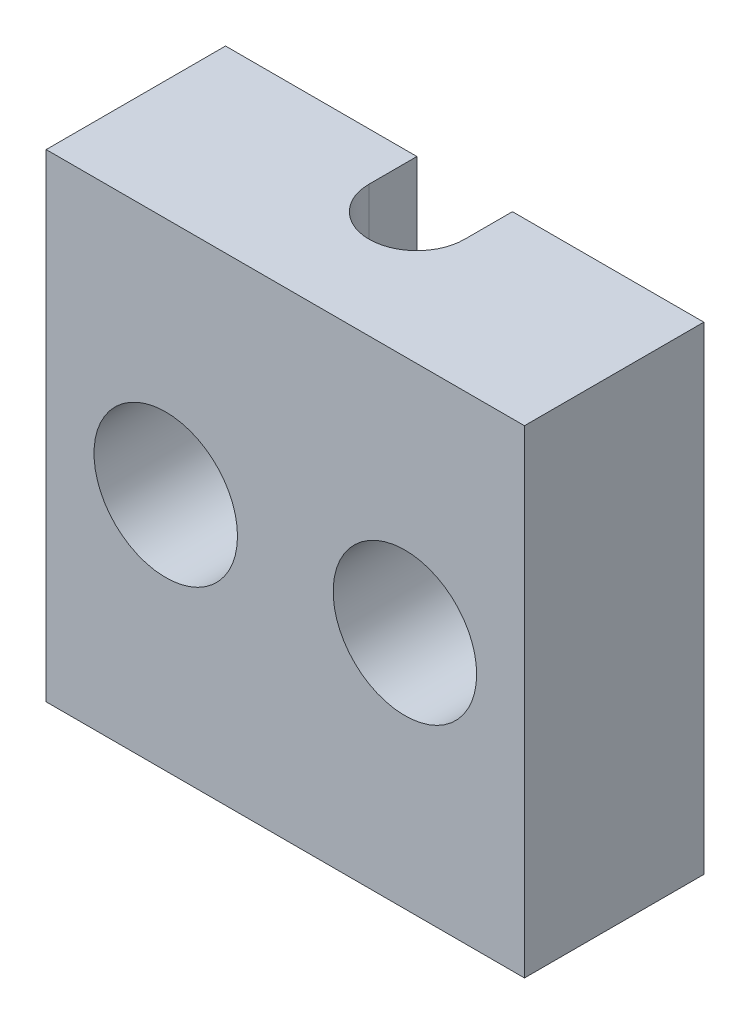
SolidWorks part; units mm, degrees
ref_plane "Front Plane" through (0, 0, 0) normal (0, 0, 1) x (1, 0, 0)
ref_plane "Top Plane" through (0, 0, 0) normal (0, 1, 0) x (1, 0, 0)
ref_plane "Right Plane" through (0, 0, 0) normal (1, 0, 0) x (0, 0, -1)
sketch "Sketch1" plane through (0, 0, 0) normal (0, 0, 1) x (1, 0, 0)
  line L1 (-5.08, 5.08) -> (5.08, 5.08)
  line L2 (-5.08, 5.08) -> (-5.08, -5.08)
  line L3 (-5.08, -5.08) -> (5.08, -5.08)
  line L4 (5.08, 5.08) -> (5.08, -5.08)
  line L5 (-5.08, 5.08) -> (5.08, -5.08) construction
  line L6 (-5.08, -5.08) -> (5.08, 5.08) construction
  point P0 (0, 0)
  point P8 (10.1614, -6.7794)
  dimension "D1" = 10.16
  dimension "D2" = 10.16
extrude "Boss-Extrude1" add sketch "Sketch1" along normal blind 3.81
sketch "Sketch2" plane through (0, 0, 3.81) normal (0, 0, 1) x (1, 0, 0)
  line L0 (-5.08, 5.08) -> (-5.08, -5.08) construction
  line L2 (-5.08, -5.08) -> (5.08, -5.08) construction
  circle A0 centre (2.54, 0) radius 1.524
  circle A1 centre (-2.54, 0) radius 1.524
  dimension "D1" = 3.048
  dimension "D2" = 5.08
  dimension "D3" = 2.54
  dimension "D4" = 5.08
extrude "Cut-Extrude1" cut sketch "Sketch2" against normal up to surface (3.81 mm away) up to face at (0, 0, 0)
sketch "Sketch3" plane through (0, -5.08, 0) normal (0, -1, 0) x (1, 0, 0)
  line L4 (-5.08, 0) -> (5.08, 0) construction
  line L5 (-1.0147, 1.016) -> (-1.0147, 0)
  line L6 (1.0147, 1.016) -> (1.0147, 0)
  line L7 (-1.0147, 0) -> (1.0147, 0)
  circle A0 centre (0, 1.016) radius 1.0147
  line M1 (-5.08, 0) -> (5.08, 0)
  dimension "D1" = 2.0295
  dimension "D2" = 1.016
extrude "Cut-Extrude3" cut sketch "Sketch3" against normal up to surface (10.16 mm away) contours A0 | A0 L5 L6 M1 up to face at (0, 5.08, 1.905)
